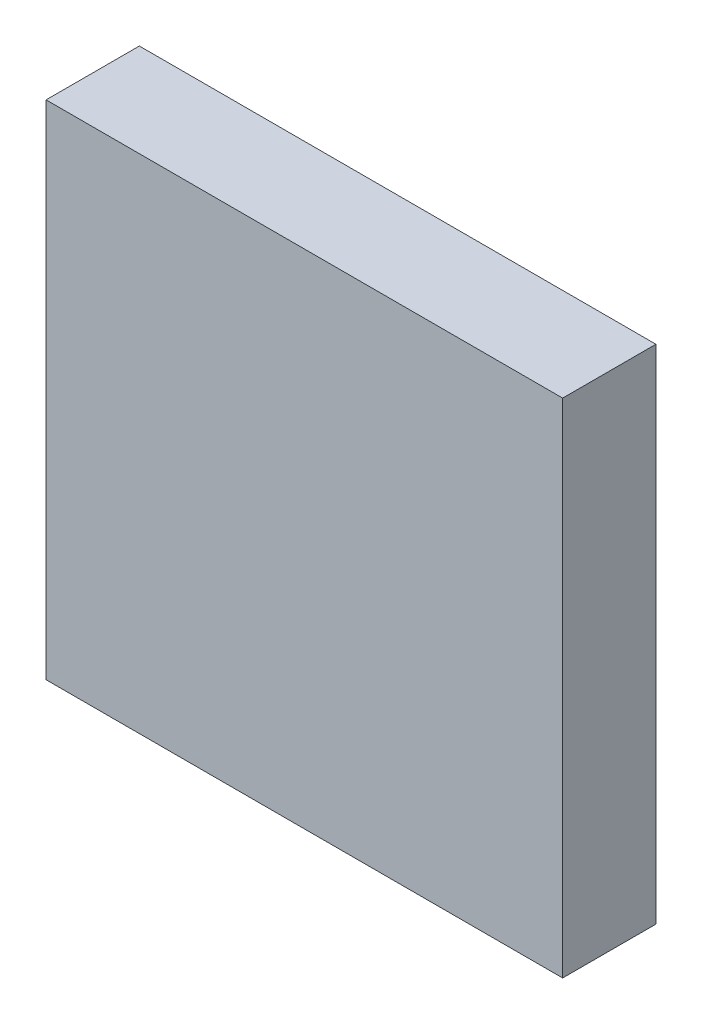
SolidWorks part; units mm, degrees
ref_plane "Front Plane" through (0, 0, 0) normal (0, 0, 1) x (1, 0, 0)
ref_plane "Top Plane" through (0, 0, 0) normal (0, 1, 0) x (1, 0, 0)
ref_plane "Right Plane" through (0, 0, 0) normal (1, 0, 0) x (0, 0, -1)
sketch "Sketch1" plane through (0, 0, 0) normal (0, 1, 0) x (1, 0, 0)
  line L1 (-76.5, 7.25) -> (283.5, 7.25)
  line L2 (-76.5, 7.25) -> (-76.5, -57.75)
  line L3 (-76.5, -57.75) -> (283.5, -57.75)
  line L4 (283.5, 7.25) -> (283.5, -57.75)
  dimension "D1" = 65
  dimension "D2" = 360
extrude "Boss-Extrude1" add sketch "Sketch1" along normal blind 350
